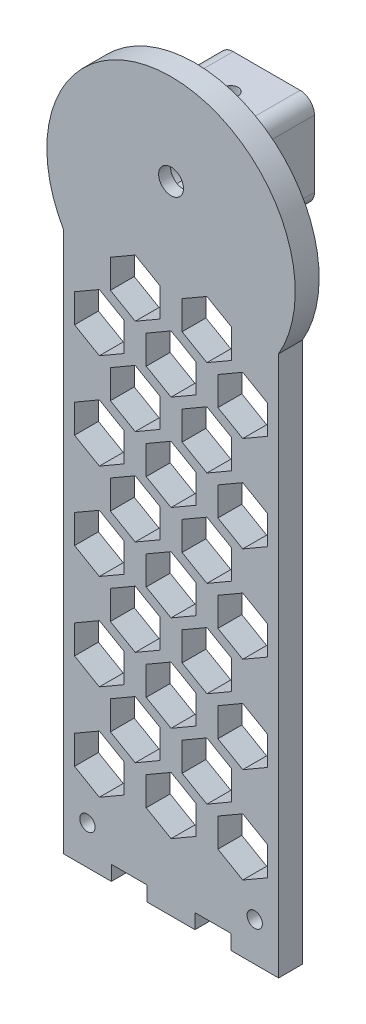
SolidWorks part; units mm, degrees
ref_plane "前视基准面" through (0, 0, 0) normal (0, 0, 1) x (1, 0, 0)
ref_plane "上视基准面" through (0, 0, 0) normal (0, 1, 0) x (1, 0, 0)
ref_plane "右视基准面" through (0, 0, 0) normal (1, 0, 0) x (0, 0, -1)
other "Configuration Table"
sketch "草图1" plane through (0, 0, 0) normal (0, 0, 1) x (1, 0, 0)
  line L0 (0, 0) -> (45, 0)
  line L1 (45, 0) -> (45, 113.1)
  line L2 (0, 0) -> (0, 113.1)
  line L3 (22.5, 126.0904) -> (22.5, 0) construction
  line L4 (0, 113.1) -> (22.5, 126.0904) construction
  line L5 (22.5, 126.0904) -> (45, 113.1) construction
  line L6 (0, 113.1) -> (45, 113.1) construction
  line L7 (19.44, 129.02) -> (25.56, 129.02)
  line L8 (22.5, 133.1) -> (22.5, 126.0904) construction
  arc A1 (0, 113.1) -> (45, 113.1) centre (22.5, 126.0904) cw
  arc A2 (25.56, 129.02) -> (19.44, 129.02) centre (22.5, 133.1) ccw
  dimension "D3" = 120
  dimension "D5" = 5.1
  dimension "D1" = 45
  dimension "D2" = 113.1
  dimension "D4" = 20
  dimension "D6" = 4.08
  dimension "D7" = 6.12
extrude "凸台-拉伸1" add sketch "草图1" along normal blind 5
sketch "草图2" plane through (0, 0, 5) normal (0, 0, 1) x (1, 0, 0)
  line L0 (0, 0) -> (45, 0) construction
  line L1 (27.5, 0) -> (35, 0)
  line L2 (27.5, 0) -> (27.5, 3.1)
  line L3 (27.5, 3.1) -> (35, 3.1)
  line L4 (35, 0) -> (35, 3.1)
  line L5 (0, 113.1) -> (0, 0) construction
  line L6 (10, 0) -> (17.5, 0)
  line L7 (10, 0) -> (10, 3.1)
  line L8 (10, 3.1) -> (17.5, 3.1)
  line L9 (17.5, 0) -> (17.5, 3.1)
  line L10 (45, 0) -> (45, 113.1) construction
  line L11 (7.5, 20) -> (22.5, 20) construction
  line L12 (7.5, 26) -> (2.3038, 23)
  line L13 (2.3038, 23) -> (2.3038, 17)
  line L14 (2.3038, 17) -> (7.5, 14)
  line L15 (7.5, 14) -> (12.6962, 17)
  line L16 (12.6962, 17) -> (12.6962, 23)
  line L17 (12.6962, 23) -> (7.5, 26)
  line L18 (22.5, 26) -> (17.3038, 23)
  line L19 (17.3038, 23) -> (17.3038, 17)
  line L20 (17.3038, 17) -> (22.5, 14)
  line L21 (22.5, 14) -> (27.6962, 17)
  line L22 (27.6962, 17) -> (27.6962, 23)
  line L23 (27.6962, 23) -> (22.5, 26)
  line L24 (37.5, 26) -> (32.3038, 23)
  line L25 (32.3038, 23) -> (32.3038, 17)
  line L26 (32.3038, 17) -> (37.5, 14)
  line L27 (37.5, 14) -> (42.6962, 17)
  line L28 (42.6962, 17) -> (42.6962, 23)
  line L29 (42.6962, 23) -> (37.5, 26)
  line L30 (22.5, 20) -> (37.5, 20) construction
  line L43 (15, 56) -> (9.8038, 53)
  line L44 (15, 36) -> (9.8038, 33)
  line L45 (9.8038, 33) -> (9.8038, 27)
  line L46 (9.8038, 27) -> (15, 24)
  line L47 (15, 24) -> (20.1962, 27)
  line L48 (20.1962, 27) -> (20.1962, 33)
  line L49 (20.1962, 33) -> (15, 36)
  line L50 (30, 36) -> (24.8038, 33)
  line L51 (24.8038, 33) -> (24.8038, 27)
  line L52 (24.8038, 27) -> (30, 24)
  line L53 (30, 24) -> (35.1962, 27)
  line L54 (35.1962, 27) -> (35.1962, 33)
  line L55 (35.1962, 33) -> (30, 36)
  line L56 (9.8038, 53) -> (9.8038, 47)
  line L57 (9.8038, 47) -> (15, 44)
  line L58 (15, 44) -> (20.1962, 47)
  line L59 (20.1962, 47) -> (20.1962, 53)
  line L60 (20.1962, 53) -> (15, 56)
  line L61 (30, 56) -> (24.8038, 53)
  line L62 (24.8038, 53) -> (24.8038, 47)
  line L63 (24.8038, 47) -> (30, 44)
  line L64 (30, 44) -> (35.1962, 47)
  line L65 (35.1962, 47) -> (35.1962, 53)
  line L66 (35.1962, 53) -> (30, 56)
  line L67 (37.5, 46) -> (32.3038, 43)
  line L68 (32.3038, 43) -> (32.3038, 37)
  line L69 (32.3038, 37) -> (37.5, 34)
  line L70 (37.5, 34) -> (42.6962, 37)
  line L71 (42.6962, 37) -> (42.6962, 43)
  line L72 (42.6962, 43) -> (37.5, 46)
  line L73 (22.5, 46) -> (17.3038, 43)
  line L74 (17.3038, 43) -> (17.3038, 37)
  line L75 (17.3038, 37) -> (22.5, 34)
  line L76 (22.5, 34) -> (27.6962, 37)
  line L77 (27.6962, 37) -> (27.6962, 43)
  line L78 (27.6962, 43) -> (22.5, 46)
  line L79 (7.5, 46) -> (2.3038, 43)
  line L80 (2.3038, 43) -> (2.3038, 37)
  line L81 (2.3038, 37) -> (7.5, 34)
  line L82 (7.5, 34) -> (12.6962, 37)
  line L83 (12.6962, 37) -> (12.6962, 43)
  line L84 (12.6962, 43) -> (7.5, 46)
  line L85 (15, 76) -> (9.8038, 73)
  line L86 (9.8038, 73) -> (9.8038, 67)
  line L87 (9.8038, 67) -> (15, 64)
  line L88 (15, 64) -> (20.1962, 67)
  line L89 (20.1962, 67) -> (20.1962, 73)
  line L90 (20.1962, 73) -> (15, 76)
  line L91 (30, 76) -> (24.8038, 73)
  line L92 (24.8038, 73) -> (24.8038, 67)
  line L93 (24.8038, 67) -> (30, 64)
  line L94 (30, 64) -> (35.1962, 67)
  line L95 (35.1962, 67) -> (35.1962, 73)
  line L96 (35.1962, 73) -> (30, 76)
  line L97 (37.5, 66) -> (32.3038, 63)
  line L98 (32.3038, 63) -> (32.3038, 57)
  line L99 (32.3038, 57) -> (37.5, 54)
  line L100 (37.5, 54) -> (42.6962, 57)
  line L101 (42.6962, 57) -> (42.6962, 63)
  line L102 (42.6962, 63) -> (37.5, 66)
  line L103 (22.5, 66) -> (17.3038, 63)
  line L104 (17.3038, 63) -> (17.3038, 57)
  line L105 (17.3038, 57) -> (22.5, 54)
  line L106 (22.5, 54) -> (27.6962, 57)
  line L107 (27.6962, 57) -> (27.6962, 63)
  line L108 (27.6962, 63) -> (22.5, 66)
  line L109 (7.5, 66) -> (2.3038, 63)
  line L110 (2.3038, 63) -> (2.3038, 57)
  line L111 (2.3038, 57) -> (7.5, 54)
  line L112 (7.5, 54) -> (12.6962, 57)
  line L113 (12.6962, 57) -> (12.6962, 63)
  line L114 (12.6962, 63) -> (7.5, 66)
  line L115 (15, 96) -> (9.8038, 93)
  line L116 (9.8038, 93) -> (9.8038, 87)
  line L117 (9.8038, 87) -> (15, 84)
  line L118 (15, 84) -> (20.1962, 87)
  line L119 (20.1962, 87) -> (20.1962, 93)
  line L120 (20.1962, 93) -> (15, 96)
  line L121 (30, 96) -> (24.8038, 93)
  line L122 (24.8038, 93) -> (24.8038, 87)
  line L123 (24.8038, 87) -> (30, 84)
  line L124 (30, 84) -> (35.1962, 87)
  line L125 (35.1962, 87) -> (35.1962, 93)
  line L126 (35.1962, 93) -> (30, 96)
  line L127 (37.5, 86) -> (32.3038, 83)
  line L128 (32.3038, 83) -> (32.3038, 77)
  line L129 (32.3038, 77) -> (37.5, 74)
  line L130 (37.5, 74) -> (42.6962, 77)
  line L131 (42.6962, 77) -> (42.6962, 83)
  line L132 (42.6962, 83) -> (37.5, 86)
  line L133 (22.5, 86) -> (17.3038, 83)
  line L134 (17.3038, 83) -> (17.3038, 77)
  line L135 (17.3038, 77) -> (22.5, 74)
  line L136 (22.5, 74) -> (27.6962, 77)
  line L137 (27.6962, 77) -> (27.6962, 83)
  line L138 (27.6962, 83) -> (22.5, 86)
  line L139 (7.5, 86) -> (2.3038, 83)
  line L140 (2.3038, 83) -> (2.3038, 77)
  line L141 (2.3038, 77) -> (7.5, 74)
  line L142 (7.5, 74) -> (12.6962, 77)
  line L143 (12.6962, 77) -> (12.6962, 83)
  line L144 (12.6962, 83) -> (7.5, 86)
  line L145 (15, 116) -> (9.8038, 113)
  line L146 (9.8038, 113) -> (9.8038, 107)
  line L147 (9.8038, 107) -> (15, 104)
  line L148 (15, 104) -> (20.1962, 107)
  line L149 (20.1962, 107) -> (20.1962, 113)
  line L150 (20.1962, 113) -> (15, 116)
  line L151 (30, 116) -> (24.8038, 113)
  line L152 (24.8038, 113) -> (24.8038, 107)
  line L153 (24.8038, 107) -> (30, 104)
  line L154 (30, 104) -> (35.1962, 107)
  line L155 (35.1962, 107) -> (35.1962, 113)
  line L156 (35.1962, 113) -> (30, 116)
  line L157 (37.5, 106) -> (32.3038, 103)
  line L158 (32.3038, 103) -> (32.3038, 97)
  line L159 (32.3038, 97) -> (37.5, 94)
  line L160 (37.5, 94) -> (42.6962, 97)
  line L161 (42.6962, 97) -> (42.6962, 103)
  line L162 (42.6962, 103) -> (37.5, 106)
  line L163 (22.5, 106) -> (17.3038, 103)
  line L164 (17.3038, 103) -> (17.3038, 97)
  line L165 (17.3038, 97) -> (22.5, 94)
  line L166 (22.5, 94) -> (27.6962, 97)
  line L167 (27.6962, 97) -> (27.6962, 103)
  line L168 (27.6962, 103) -> (22.5, 106)
  line L169 (7.5, 106) -> (2.3038, 103)
  line L170 (2.3038, 103) -> (2.3038, 97)
  line L171 (2.3038, 97) -> (7.5, 94)
  line L172 (7.5, 94) -> (12.6962, 97)
  line L173 (12.6962, 97) -> (12.6962, 103)
  line L174 (12.6962, 103) -> (7.5, 106)
  circle A0 centre (40, 8.1) radius 1.6
  circle A1 centre (5, 8.1) radius 1.6
  circle A2 centre (7.5, 20) radius 5.1962 construction
  circle A3 centre (22.5, 20) radius 5.1962 construction
  circle A4 centre (37.5, 20) radius 5.1962 construction
  circle A5 centre (15, 30) radius 5.1962 construction
  circle A6 centre (30, 30) radius 5.1962 construction
  dimension "D7" = 3.2
  dimension "D1" = 3.1
  dimension "D2" = 3.1
  dimension "D3" = 10
  dimension "D4" = 10
  dimension "D5" = 10
  dimension "D6" = 7.5
  dimension "D8" = 5
  dimension "D9" = 5
  dimension "D10" = 5
  dimension "D11" = 5
  dimension "D12" = 22.5
  dimension "D13" = 15
  dimension "D14" = 15
  dimension "D15" = 6
  dimension "D16" = 20
  dimension "D17" = 15
  dimension "D18" = 15
  dimension "D19" = 30
  dimension "D20" = 30
  dimension "D21" = 5
extrude "切除-拉伸1" cut sketch "草图2" against normal up to next (5 mm away)
sketch "草图3" plane through (0, 0, 5) normal (0, 0, 1) x (1, 0, 0)
  line L0 (19.44, 129.02) -> (25.56, 129.02)
  arc A0 (19.44, 129.02) -> (25.56, 129.02) centre (22.5, 133.1) cw
  circle A1 centre (22.5, 133.1) radius 2.6
  dimension "D1" = 5.2
extrude "凸台-拉伸2" add sketch "草图3" against normal blind 2.5
sketch "草图4" plane through (0, 0, 0) normal (0, 0, -1) x (-1, 0, 0)
  line L0 (-19.44, 129.02) -> (-25.56, 129.02) construction
  line L1 (-25.56, 129.02) -> (-19.44, 129.02)
  line L3 (-12.5, 123.1) -> (-32.5, 123.1)
  line L4 (-12.5, 123.1) -> (-12.5, 143.1)
  line L5 (-12.5, 143.1) -> (-32.5, 143.1)
  line L6 (-32.5, 123.1) -> (-32.5, 143.1)
  line L7 (-12.5, 123.1) -> (-32.5, 143.1) construction
  line L8 (-12.5, 143.1) -> (-32.5, 123.1) construction
  arc A0 (-19.44, 129.02) -> (-25.56, 129.02) centre (-22.5, 133.1) ccw
  dimension "D1" = 20
extrude "凸台-拉伸3" add sketch "草图4" along normal blind 15
sketch "草图5" plane through (0, 123.1, 0) normal (0, -1, 0) x (1, 0, 0)
  line L1 (12.5, -15) -> (12.5, 0) construction
  line L2 (17.5, 0) -> (27.5, 0) construction
  circle A0 centre (22.5, -7.5) radius 1.55
  dimension "D1" = 3.1
  dimension "D2" = 10
  dimension "D3" = 7.5
extrude "切除-拉伸2" cut sketch "草图5" against normal up to surface (20 mm away) up to face at (22.5, 143.1, -7.5)
fillet "圆角2" radius 3 8 edges at (22.5, 123.1, 0) (12.5, 133.1, 0) (32.5, 133.1, 0) (22.5, 143.1, 0) (32.5, 123.1, -7.5) (32.5, 143.1, -7.5) (12.5, 143.1, -7.5) (12.5, 123.1, -7.5)
